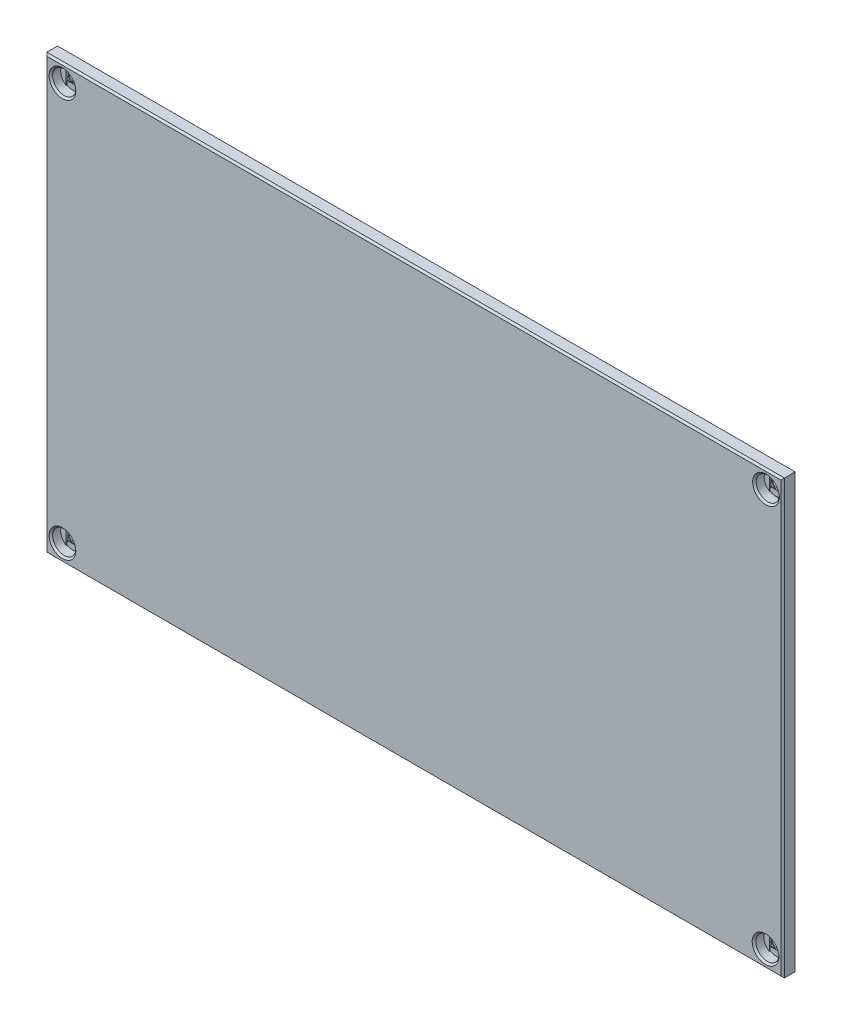
SolidWorks part; units mm, degrees
ref_plane "Front Plane" through (0, 0, 0) normal (0, 0, 1) x (1, 0, 0)
ref_plane "Top Plane" through (0, 0, 0) normal (0, 1, 0) x (1, 0, 0)
ref_plane "Right Plane" through (0, 0, 0) normal (1, 0, 0) x (0, 0, -1)
sketch "Sketch1" plane through (0, 0, 0) normal (0, 0, 1) x (1, 0, 0)
  line L0 (82.95, -11.1) -> (82.95, -18.5) construction
  line L1 (-82.85, -11.1) -> (-82.85, -18.5) construction
  line L2 (-83, -108) -> (-83, -100) construction
  line L3 (-75, -108) -> (-83, -108) construction
  line L4 (75, -108) -> (83, -108) construction
  line L5 (-82.25, -10.5) -> (82.35, -10.5) construction
  line L6 (82.95, -11.1) -> (82.95, -18.5)
  line L7 (-82.85, -11.1) -> (-82.85, -18.5)
  line L8 (-83, -108) -> (-83, -100)
  line L9 (-75, -108) -> (-83, -108)
  line L10 (75, -108) -> (83, -108)
  line L11 (-82.25, -10.5) -> (82.35, -10.5)
  circle A0 centre (-79, -14.5) radius 2.55 construction
  circle A1 centre (79.1, -14.5) radius 2.55
  circle A2 centre (79.1, -14.5) radius 2.55
  circle A3 centre (-79, -104) radius 2.15 construction
  circle A4 centre (79, -104) radius 2.55 construction
  circle A5 centre (-79, -14.5) radius 2.55
  circle A6 centre (-79, -104) radius 2.15
  circle A7 centre (79, -104) radius 2.55
  dimension "D1" = 0
sketch "Sketch2" plane through (0, 0, 0) normal (0, 0, 1) x (1, 0, 0)
  line L0 (-75, -108) -> (-83, -108) construction
  line L1 (-82.9, -10.6) -> (82.85, -10.6)
  line L2 (-82.9, -10.6) -> (-82.9, -107.9)
  line L3 (-82.9, -107.9) -> (82.85, -107.9)
  line L4 (82.85, -10.6) -> (82.85, -107.9)
  line L5 (-83, -108) -> (-83, -100) construction
  line L6 (-82.25, -10.5) -> (82.35, -10.5) construction
  line L7 (82.95, -11.1) -> (82.95, -18.5) construction
  circle A0 centre (-79, -14.5) radius 1.35
  circle A1 centre (79.1, -14.5) radius 1.35
  circle A2 centre (79, -104) radius 1.35
  circle A3 centre (-79, -104) radius 1.35
  point P12 (82.95, -14.8)
  dimension "D5" = 2.7
  dimension "D1" = 0.1
  dimension "D2" = 0.1
  dimension "D3" = 0.1
  dimension "D4" = 0.1
extrude "Boss-Extrude1" add sketch "Sketch2" along normal blind 2.8
sketch "Sketch3" plane through (0, 0, 2.8) normal (0, 0, 1) x (1, 0, 0)
  circle A0 centre (-79, -14.5) radius 2.6
  circle A1 centre (-79, -104) radius 2.6
  circle A2 centre (79, -104) radius 2.6
  circle A3 centre (79.1, -14.5) radius 2.6
  dimension "D1" = 5.2
extrude "Cut-Extrude1" cut sketch "Sketch3" against normal blind 2.2
sketch "Sketch4" plane through (0, 0, 0.6) normal (0, 0, 1) x (1, 0, 0)
  line L6 (-80.35, -16.722) -> (-80.35, -12.278)
  line L8 (-77.65, -16.722) -> (-77.65, -12.278)
  line L9 (-80.35, -16.722) -> (-77.65, -12.278) construction
  line L10 (-80.35, -12.278) -> (-77.65, -16.722) construction
  circle A6 centre (-79, -14.5) radius 2.6 construction
  circle A7 centre (-79, -14.5) radius 1.35 construction
  arc A8 (-77.65, -12.278) -> (-80.35, -12.278) centre (-79, -14.5) ccw
  arc A9 (-80.35, -16.722) -> (-77.65, -16.722) centre (-79, -14.5) ccw
  point P0 (-79, -14.5)
extrude "Cut-Extrude2" cut sketch "Sketch4" against normal blind 0.2
sketch "Sketch5" plane through (0, 0, 0.4) normal (0, 0, 1) x (1, 0, 0)
  line L0 (-77.65, -16.722) -> (-77.65, -12.278) construction
  line L1 (-80.35, -15.85) -> (-77.65, -15.85)
  line L2 (-80.35, -15.85) -> (-80.35, -13.15)
  line L3 (-80.35, -13.15) -> (-77.65, -13.15)
  line L4 (-77.65, -15.85) -> (-77.65, -13.15)
  line L5 (-80.35, -15.85) -> (-77.65, -13.15) construction
  line L6 (-80.35, -13.15) -> (-77.65, -15.85) construction
  arc A0 (-77.65, -14.5) -> (-80.35, -14.5) centre (-79, -14.5) ccw construction
  point P0 (-79, -14.5)
extrude "Cut-Extrude3" cut sketch "Sketch5" against normal blind 0.2
ref_plane "Plane1" through (0, -59.25, 0) normal (0, 1, 0) x (1, 0, 0)
mirror "Mirror1" about plane through (0, -59.25, 0) normal (0, 1, 0) of "Cut-Extrude3", "Cut-Extrude2"
mirror "Mirror2" about plane through (0, 0, 0) normal (1, 0, 0) of "Mirror1", "Cut-Extrude2", "Cut-Extrude3"
chamfer "Chamfer1" distance 0.4 angle 45 8 edges at (81.7, -14.5, 2.8) (81.6, -104, 2.8) (-76.4, -104, 2.8) (-76.4, -14.5, 2.8) (-0.025, -107.9, 2.8) (82.85, -59.25, 2.8) (-0.025, -10.6, 2.8) (-82.9, -59.25, 2.8)
